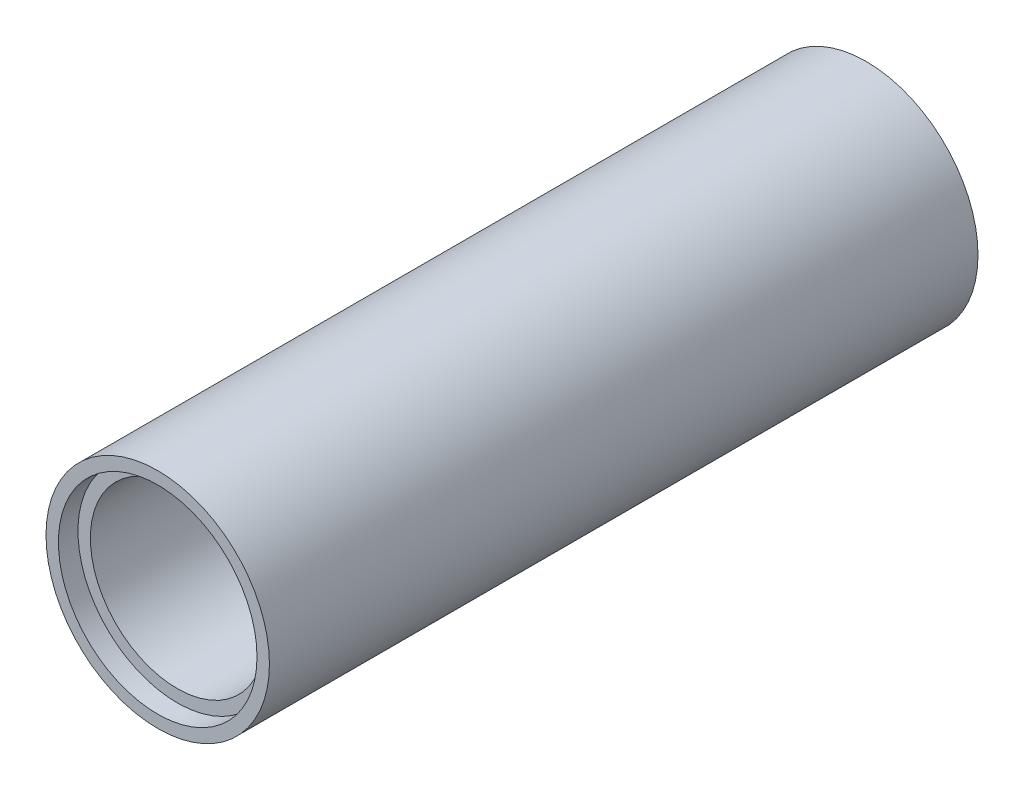
SolidWorks part; units mm, degrees
ref_plane "Front Plane" through (0, 0, 0) normal (0, 0, 1) x (1, 0, 0)
ref_plane "Top Plane" through (0, 0, 0) normal (0, 1, 0) x (1, 0, 0)
ref_plane "Right Plane" through (0, 0, 0) normal (1, 0, 0) x (0, 0, -1)
sketch "Sketch1" plane through (0, 0, 0) normal (0, 0, 1) x (1, 0, 0)
  circle A0 centre (0, 0) radius 57.15
  circle A1 centre (0, 0) radius 44.45
  dimension "D1" = 114.3
  dimension "D2" = 88.9
extrude "Boss-Extrude1" add sketch "Sketch1" along normal blind 362.5
sketch "Sketch2" plane through (0, 0, 362.5) normal (0, 0, 1) x (1, 0, 0)
  circle A0 centre (0, 0) radius 50.8
  circle A2 centre (0, 0) radius 44.45 construction
  circle A3 centre (0, 0) radius 44.45
  dimension "D1" = 101.6
extrude "Cut-Extrude1" cut sketch "Sketch2" against normal blind 10
